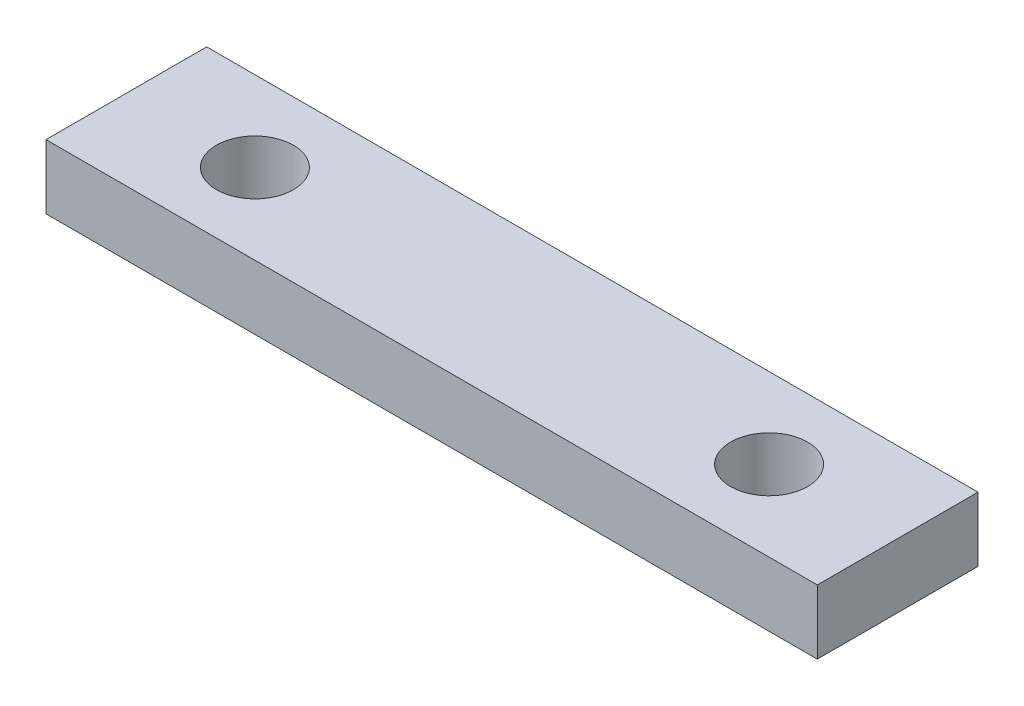
SolidWorks part; units mm, degrees
material "Cast Alloy Steel"
ref_plane "Front Plane" through (0, 0, 0) normal (0, 0, 1) x (1, 0, 0)
ref_plane "Top Plane" through (0, 0, 0) normal (0, 1, 0) x (1, 0, 0)
ref_plane "Right Plane" through (0, 0, 0) normal (1, 0, 0) x (0, 0, -1)
sketch "Sketch1" plane through (0, 0, 0) normal (0, 1, 0) x (1, 0, 0)
  line L1 (-60, 12.5) -> (60, 12.5)
  line L2 (-60, 12.5) -> (-60, -12.5)
  line L3 (-60, -12.5) -> (60, -12.5)
  line L4 (60, 12.5) -> (60, -12.5)
  circle A0 centre (40, 0) radius 6
  circle A1 centre (-40, 0) radius 6
  point P9 (0, 0)
  dimension "D7" = 12
  dimension "D8" = 12
  dimension "D1" = 120
  dimension "D2" = 25
  dimension "D3" = 12.5
  dimension "D4" = 60
  dimension "D5" = 40
  dimension "D6" = 40
extrude "Boss-Extrude1" add sketch "Sketch1" along normal blind 10 contours L3 L4 L1 L2
